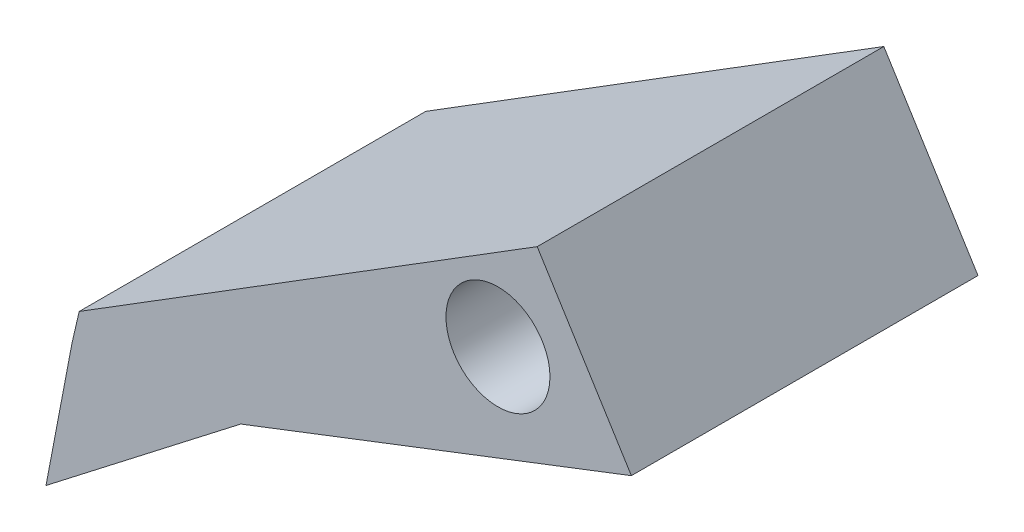
SolidWorks part; units mm, degrees
ref_plane "前视基准面" through (0, 0, 0) normal (0, 0, 1) x (1, 0, 0)
ref_plane "上视基准面" through (0, 0, 0) normal (0, 1, 0) x (1, 0, 0)
ref_plane "右视基准面" through (0, 0, 0) normal (1, 0, 0) x (0, 0, -1)
sketch "草图1" plane through (0, 0, 0) normal (0, 0, 1) x (1, 0, 0)
  line L1 (0, -20.331) -> (0, 23.329) construction
  line L39 (0, 18.0913) -> (0.753, 22.0375)
  line L40 (0.753, 22.0375) -> (0.958, 22.9189)
  line L41 (0.958, 22.9189) -> (14.1711, 31.1446)
  line L42 (14.1711, 31.1446) -> (16.8882, 26.7802)
  line L44 (0, 18.0913) -> (5.6187, 22.4357)
  line L45 (5.6187, 22.4357) -> (16.8882, 26.7802)
  circle A0 centre (13.0393, 28.0753) radius 1.5
  dimension "D1" = 3
extrude "凸台-拉伸1" add sketch "草图1" along normal blind 10
